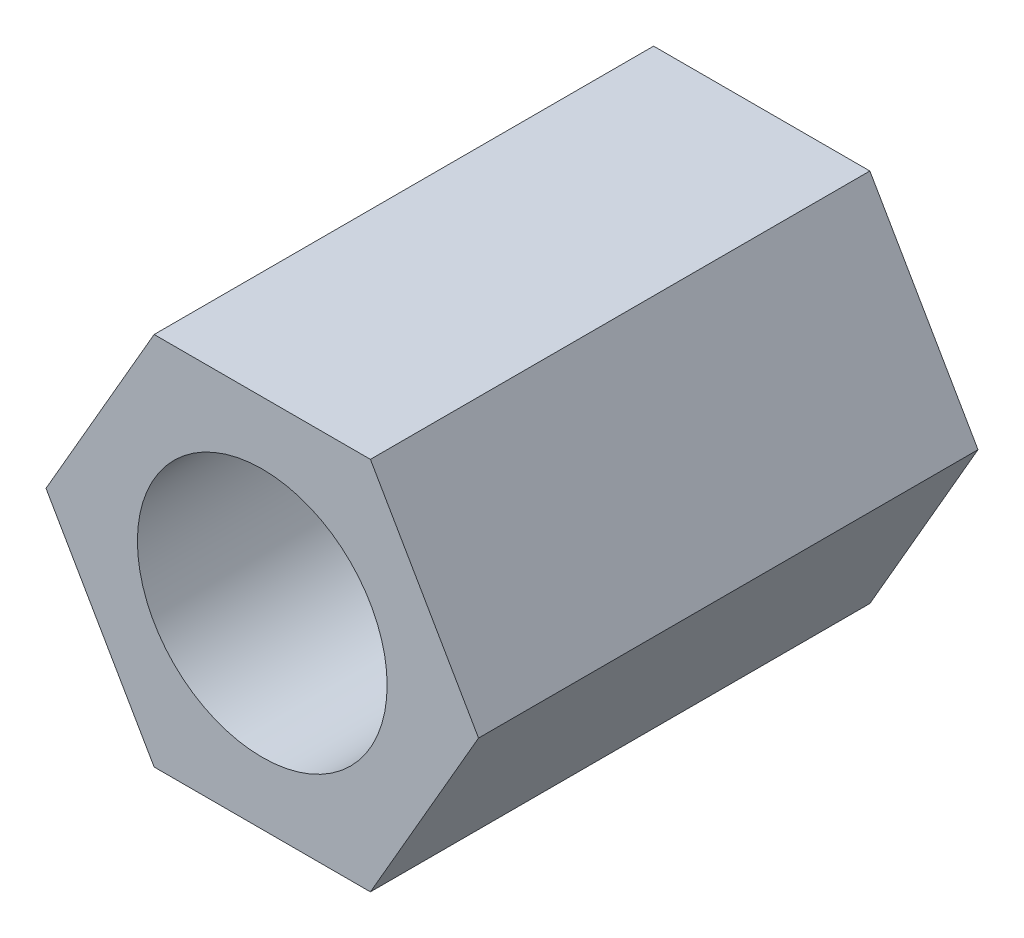
SolidWorks part; units mm, degrees
ref_plane "前视基准面" through (0, 0, 0) normal (0, 0, 1) x (1, 0, 0)
ref_plane "上视基准面" through (0, 0, 0) normal (0, 1, 0) x (1, 0, 0)
ref_plane "右视基准面" through (0, 0, 0) normal (1, 0, 0) x (0, 0, -1)
sketch "草图1" plane through (0, 0, 0) normal (0, 0, 1) x (1, 0, 0)
  line L1 (1.7321, 0) -> (0.866, 1.5)
  line L2 (0.866, 1.5) -> (-0.866, 1.5)
  line L3 (-0.866, 1.5) -> (-1.7321, 0)
  line L4 (-1.7321, 0) -> (-0.866, -1.5)
  line L5 (-0.866, -1.5) -> (0.866, -1.5)
  line L6 (0.866, -1.5) -> (1.7321, 0)
  circle A0 centre (0, 0) radius 1
  circle A1 centre (0, 0) radius 1.5 construction
  dimension "D1" = 2
  dimension "D2" = 3
extrude "凸台-拉伸1" add sketch "草图1" along normal blind 4
